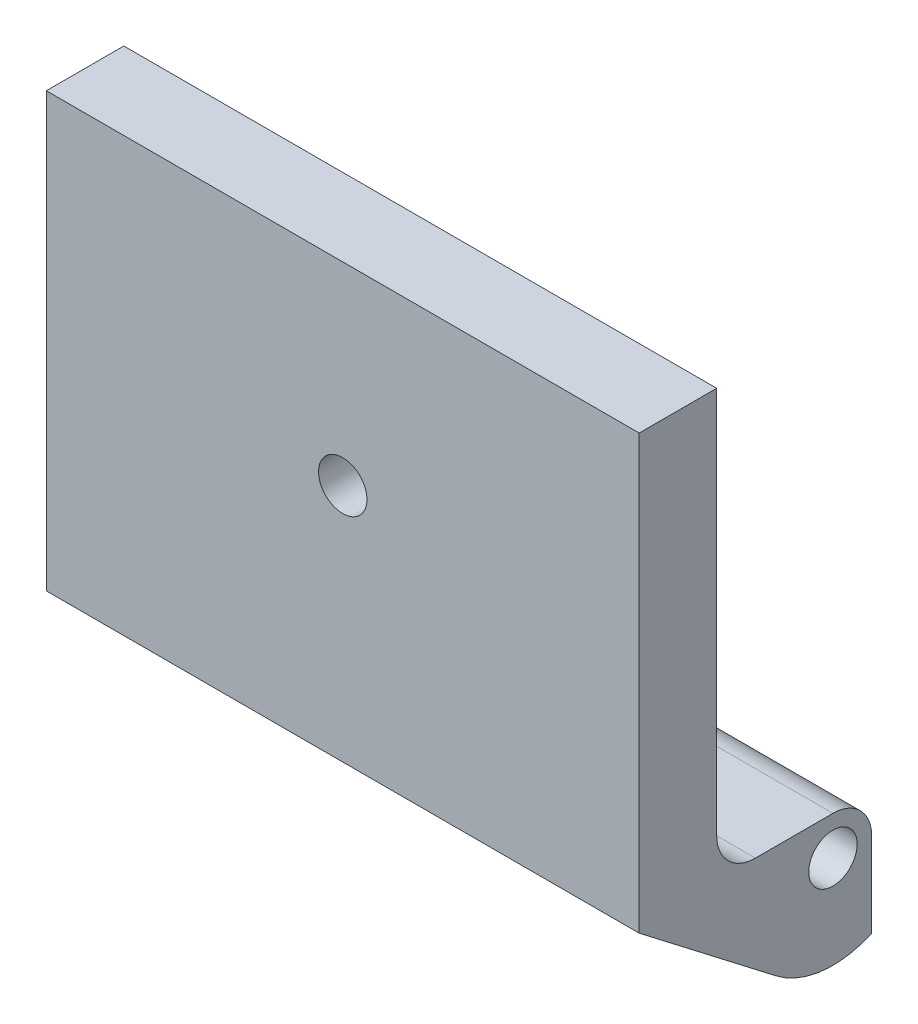
SolidWorks part; units mm, degrees
ref_plane "Front Plane" through (0, 0, 0) normal (0, 0, 1) x (1, 0, 0)
ref_plane "Top Plane" through (0, 0, 0) normal (0, 1, 0) x (1, 0, 0)
ref_plane "Right Plane" through (0, 0, 0) normal (1, 0, 0) x (0, 0, -1)
sketch "Sketch1" plane through (0, 0, 0) normal (0, 1, 0) x (1, 0, 0)
  line L1 (19.431, -12.7) -> (-19.431, -12.7)
  line L2 (19.431, -12.7) -> (19.431, 12.7)
  line L3 (19.431, 12.7) -> (-19.431, 12.7)
  line L4 (-19.431, -12.7) -> (-19.431, 12.7)
  line L5 (19.431, -12.7) -> (-19.431, 12.7) construction
  line L6 (19.431, 12.7) -> (-19.431, -12.7) construction
  point P0 (0, 0)
  dimension "D1" = 25.4
  dimension "D2" = 38.862
extrude "Boss-Extrude1" add sketch "Sketch1" along normal blind 17.78
sketch "Sketch2" plane through (19.431, 0, 0) normal (1, 0, 0) x (0, 0, -1)
  line L0 (-12.7, 0) -> (12.7, 0) construction
  line L2 (-12.7, 17.78) -> (-12.7, 0) construction
  circle A0 centre (0, 6.35) radius 1.5875
  point P4 (0, 0)
  point P6 (-12.7, 6.8444)
  dimension "D3" = 3.175
  dimension "D1" = 6.35
  dimension "D2" = 12.7
extrude "Cut-Extrude1" cut sketch "Sketch2" against normal through all
sketch "Sketch3" plane through (19.431, 0, 0) normal (1, 0, 0) x (0, 0, -1)
  line L1 (-12.7, 17.78) -> (12.7, 17.78) construction
  line L2 (-7.62, 17.78) -> (-7.62, 11.43)
  line L3 (-5.08, 8.89) -> (0, 8.89)
  line L4 (2.54, 6.35) -> (2.54, 0)
  line L5 (-12.7, 0) -> (12.7, 0) construction
  line L6 (12.7, 17.78) -> (12.7, 0) construction
  line L7 (2.54, 0) -> (12.7, 0)
  line L8 (12.7, 17.78) -> (12.7, 0)
  line L9 (-7.62, 17.78) -> (12.7, 17.78)
  circle A0 centre (0, 6.35) radius 1.5875 construction
  arc A1 (-5.08, 8.89) -> (-7.62, 11.43) centre (-5.08, 11.43) cw
  arc A2 (2.54, 6.35) -> (0, 8.89) centre (0, 6.35) ccw
  dimension "D1" = 2.54
  dimension "D3" = 2.54
  dimension "D2" = 2.54
  dimension "D4" = 5.08
extrude "Cut-Extrude2" cut sketch "Sketch3" against normal through all
sketch "Sketch4" plane through (0, 0, 7.62) normal (0, 0, -1) x (-1, 0, 0)
  line L0 (19.431, 17.78) -> (19.431, 11.43) construction
  line L1 (-19.431, 11.43) -> (19.431, 11.43)
  line L2 (-19.431, 11.43) -> (-19.431, 36.83)
  line L3 (-19.431, 36.83) -> (19.431, 36.83)
  line L4 (19.431, 11.43) -> (19.431, 36.83)
  dimension "D1" = 25.4
extrude "Boss-Extrude2" add sketch "Sketch4" against normal up to surface (5.08 mm away) up to face at (0, 8.89, 12.7)
sketch "Sketch5" plane through (0, 0, 7.62) normal (0, 0, -1) x (-1, 0, 0)
  line L0 (-19.431, 36.83) -> (19.431, 11.43) construction
  line L1 (-19.431, 36.83) -> (19.431, 36.83) construction
  line L2 (-19.431, 36.83) -> (-19.431, 11.43) construction
  line L3 (-19.431, 11.43) -> (19.431, 11.43) construction
  line L4 (19.431, 36.83) -> (19.431, 11.43) construction
  line L5 (19.431, 11.43) -> (19.431, 36.83) construction
  line L6 (19.431, 36.83) -> (-19.431, 11.43) construction
  circle A0 centre (0, 24.13) radius 1.5875
  dimension "D1" = 3.175
extrude "Cut-Extrude3" cut sketch "Sketch5" against normal blind 25.4
sketch "Sketch6" plane through (19.431, 0, 0) normal (1, 0, 0) x (0, 0, -1)
  line L0 (-3.8746, 1.3191) -> (-12.7, 8.1161)
  line L1 (-12.7, 36.83) -> (-12.7, 0) construction
  line L8 (-7.62, 11.43) -> (-7.62, 36.83)
  line L9 (-7.62, 36.83) -> (-12.7, 36.83)
  line L10 (-12.7, 36.83) -> (-12.7, 0)
  line L11 (-12.7, 0) -> (2.54, 0)
  line L12 (2.54, 0) -> (2.54, 6.35)
  line L13 (0, 8.89) -> (-5.08, 8.89)
  line L16 (-12.7, 8.1161) -> (-12.7, 0)
  line L17 (-12.7, 0) -> (2.54, 0)
  line L18 (2.54, 0) -> (2.54, 0.5301)
  arc A1 (-3.8746, 1.3191) -> (2.54, 0.5301) centre (0, 6.35) ccw
  arc A4 (-7.62, 11.43) -> (-5.08, 8.89) centre (-5.08, 11.43) ccw
  arc A5 (2.54, 6.35) -> (0, 8.89) centre (0, 6.35) ccw
  point P5 (-4.4995, 1.8692)
  point P8 (-12.7, 8.1161)
  line M14 (-12.7, 36.83) -> (-12.7, 0)
  line M15 (-12.7, 0) -> (2.54, 0)
  line M16 (2.54, 0) -> (2.54, 6.35)
  dimension "D1" = 0
extrude "Cut-Extrude4" cut sketch "Sketch6" against normal through all contours A1 L0 M14 M15 | A1 L17 M16
sketch "Sketch7" plane through (19.431, 0, 0) normal (1, 0, 0) x (0, 0, -1)
  line L1 (2.54, 6.35) -> (2.54, 0.5301) construction
  line L2 (-12.545, 8.3174) -> (-3.7196, 1.5204)
  line L3 (-12.7, 8.4367) -> (-3.7196, 1.5204)
  line L4 (-12.7, 36.83) -> (-12.7, 8.1161) construction
  line L5 (-3.8746, 1.3191) -> (-12.7, 8.1161) construction
  line L6 (2.54, 0.8084) -> (2.54, 0.5301)
  line L7 (-3.8746, 1.3191) -> (-12.7, 8.1161)
  line L8 (-12.7, 8.4367) -> (-12.7, 8.1161)
  arc A1 (-3.8746, 1.3191) -> (2.54, 0.5301) centre (0, 6.35) ccw construction
  arc A2 (-3.7196, 1.5204) -> (2.4384, 0.7629) centre (0, 6.35) ccw
  arc A3 (-3.7196, 1.5204) -> (2.54, 0.8084) centre (0, 6.35) ccw
  arc A4 (-3.8746, 1.3191) -> (2.54, 0.5301) centre (0, 6.35) ccw
  point P0 (-12.7, 8.4426)
  dimension "D1" = 0.254
extrude "Cut-Extrude5" cut sketch "Sketch7" against normal through all
